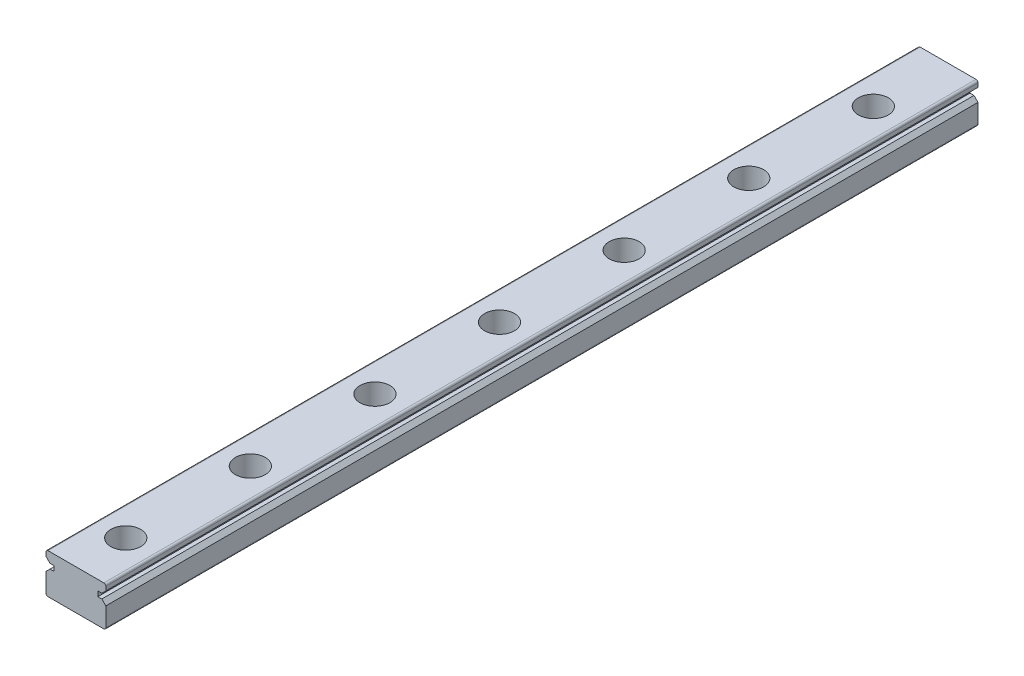
SolidWorks part; units mm, degrees
ref_plane "Front Plane" through (0, 0, 0) normal (0, 0, 1) x (1, 0, 0)
ref_plane "Top Plane" through (0, 0, 0) normal (0, 1, 0) x (1, 0, 0)
ref_plane "Right Plane" through (0, 0, 0) normal (1, 0, 0) x (0, 0, -1)
sketch "Sketch1" plane through (0, 0, 0) normal (0, 0, 1) x (1, 0, 0)
  line L0 (0, -1000) -> (0, 1.5) construction
  line L1 (-5.6, 4) -> (5.6, 4)
  line L2 (-6, 3.6) -> (-6, 2.8)
  line L3 (-5.6, -4) -> (5.6, -4)
  line L4 (6, 3.6) -> (6, 2.8)
  line L5 (-6, 4) -> (6, -4) construction
  line L6 (-6, -4) -> (6, 4) construction
  line L7 (6, 0.2) -> (6, -3.6)
  line L8 (-5.2, 2) -> (-4.4, 2)
  line L9 (-4.4, 2) -> (-4.4, 1)
  line L10 (-5.2, 1) -> (-4.4, 1)
  line L11 (4.4, 2) -> (4.4, 1)
  line L14 (-6, 0.2) -> (-6, -3.6)
  line L15 (4.4, 2) -> (5.2, 2)
  line L16 (4.4, 1) -> (5.2, 1)
  line L17 (0, 1.5) -> (0, 1001.8645) construction
  line L18 (-6, 2.8) -> (-5.2, 2)
  line L19 (-6, 0.2) -> (-5.2, 1)
  line L20 (5.2, 2) -> (6, 2.8)
  line L21 (5.2, 1) -> (6, 0.2)
  arc A0 (-6, -3.6) -> (-5.6, -4) centre (-5.6, -3.6) ccw
  arc A1 (5.6, -4) -> (6, -3.6) centre (5.6, -3.6) ccw
  arc A2 (5.6, 4) -> (6, 3.6) centre (5.6, 3.6) cw
  arc A3 (-5.6, 4) -> (-6, 3.6) centre (-5.6, 3.6) ccw
  point P0 (0, 0)
  point P13 (-6, 2)
  point P14 (6, 2)
  point P15 (6, 1)
  point P16 (-6, 1)
  dimension "D5" = 0.4
  dimension "D1" = 12
  dimension "D2" = 8
  dimension "D3" = 8.8
  dimension "D4" = 5
  dimension "D6" = 2
  dimension "D7" = 5
  dimension "D8" = 4.4
extrude "Boss-Extrude1" add sketch "Sketch1" along normal blind 300
sketch "Sketch2" plane through (0, 4, 0) normal (0, 1, 0) x (1, 0, 0)
  line L0 (5.6, -300) -> (-5.6, -300) construction
  circle A0 centre (0, -290) radius 3
  circle A1 centre (0, -265) radius 3
  circle A2 centre (0, -240) radius 3
  circle A3 centre (0, -215) radius 3
  circle A4 centre (0, -190) radius 3
  circle A5 centre (0, -165) radius 3
  circle A6 centre (0, -140) radius 3
  circle A7 centre (0, -115) radius 3
  circle A8 centre (0, -90) radius 3
  circle A9 centre (0, -65) radius 3
  circle A10 centre (0, -40) radius 3
  circle A11 centre (0, -15) radius 3
  circle A12 centre (0, 10) radius 3
  circle A13 centre (0, 35) radius 3
  circle A14 centre (0, 60) radius 3
  circle A15 centre (0, 85) radius 3
  circle A16 centre (0, 110) radius 3
  circle A17 centre (0, 135) radius 3
  point P39 (0, -300)
  dimension "D1" = 10
  dimension "D2" = 6
  dimension "D3" = 18
extrude "Cut-Extrude1" cut sketch "Sketch2" against normal blind 4.5
sketch "Sketch3" plane through (0, 4, 0) normal (0, 1, 0) x (1, 0, 0)
  line L0 (5.6, -300) -> (-5.6, -300) construction
  circle A2 centre (0, -290.0015) radius 1.75
  circle A3 centre (0, -265.0015) radius 1.75
  circle A4 centre (0, -240.0015) radius 1.75
  circle A5 centre (0, -215.0015) radius 1.75
  circle A6 centre (0, -190.0015) radius 1.75
  circle A7 centre (0, -165.0015) radius 1.75
  circle A8 centre (0, -140.0015) radius 1.75
  circle A9 centre (0, -115.0015) radius 1.75
  circle A10 centre (0, -90.0015) radius 1.75
  circle A11 centre (0, -65.0015) radius 1.75
  circle A12 centre (0, -40.0015) radius 1.75
  circle A13 centre (0, -15.0015) radius 1.75
  circle A14 centre (0, 9.9985) radius 1.75
  circle A15 centre (0, 34.9985) radius 1.75
  circle A16 centre (0, 59.9985) radius 1.75
  point P6 (0, -300)
  dimension "D1" = 3.5
  dimension "D2" = 9.9985
  dimension "D3" = 15
extrude "Cut-Extrude2" cut sketch "Sketch3" against normal through all
sketch "Sketch4" plane through (0, -4, 0) normal (0, -1, 0) x (1, 0, 0)
  line L0 (-6, 125) -> (-2, 125)
  line L1 (-6, 300) -> (-6, 0) construction
  line L2 (-2, 125) -> (-2, 127)
  line L3 (-2, 127) -> (-4, 127)
  line L4 (-4, 127) -> (0, 133)
  line L5 (0, 300) -> (0, 297.0685) construction
  line L7 (4, 127) -> (0, 133)
  line L8 (2, 127) -> (4, 127)
  line L9 (2, 125) -> (2, 127)
  line L10 (6, 125) -> (2, 125)
  line L11 (-5.6, 0) -> (5.6, 0) construction
  line L12 (6, 125) -> (29.6773, -70.0878)
  line L13 (29.6773, -70.0878) -> (-63.4726, -88.906)
  line L14 (-63.4726, -88.906) -> (-6, 125)
  dimension "D1" = 2
  dimension "D2" = 2
  dimension "D3" = 8
  dimension "D4" = 4
  dimension "D5" = 125
extrude "Cut-Extrude3" cut sketch "Sketch4" against normal blind 3
sketch "Sketch5" plane through (0, -1, 0) normal (0, -1, 0) x (1, 0, 0)
  line L1 (-6, 125) -> (6, 125)
  line L2 (-6, 125) -> (-6, 0)
  line L3 (-6, 0) -> (6, 0)
  line L4 (6, 125) -> (6, 0)
extrude "Cut-Extrude5" cut sketch "Sketch5" against normal through all
